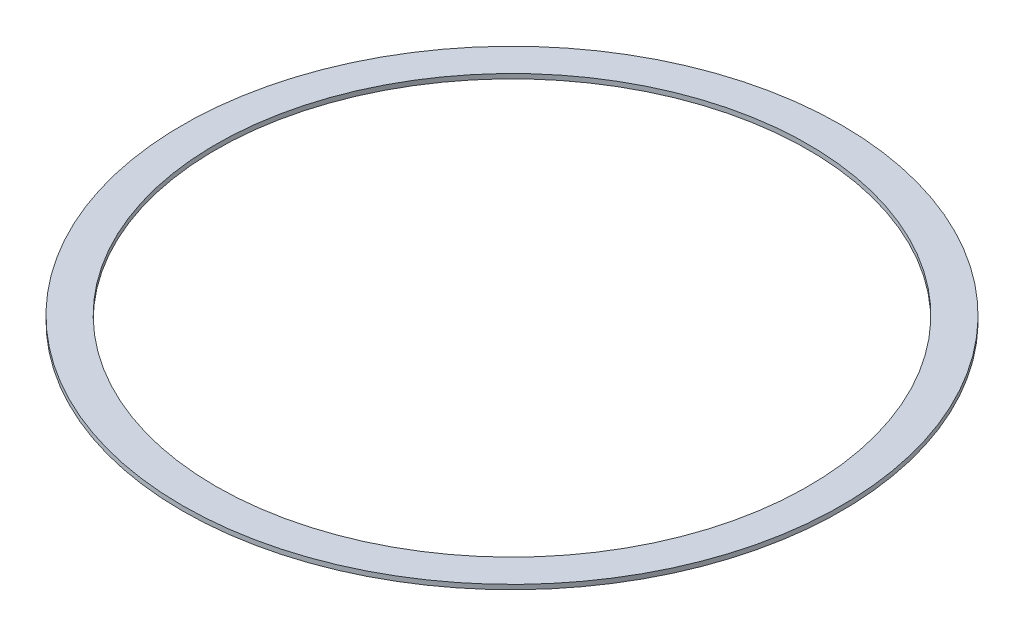
SolidWorks part; units mm, degrees
material "6061-T6 (SS)"
ref_plane "Front Plane" through (0, 0, 0) normal (0, 0, 1) x (1, 0, 0)
ref_plane "Top Plane" through (0, 0, 0) normal (0, 1, 0) x (1, 0, 0)
ref_plane "Right Plane" through (0, 0, 0) normal (1, 0, 0) x (0, 0, -1)
sketch "Sketch1" plane through (0, 0, 0) normal (0, 1, 0) x (1, 0, 0)
  circle A0 centre (0, 0) radius 162.2679
  circle A1 centre (0, 0) radius 180.5559
  dimension "D1" = 361.1118
  dimension "D2" = 324.5358
extrude "Boss-Extrude1" add sketch "Sketch1" along normal blind 2.54
ref_plane "Plane1" through (0, 1.27, 0) normal (0, 1, 0) x (1, 0, 0)
